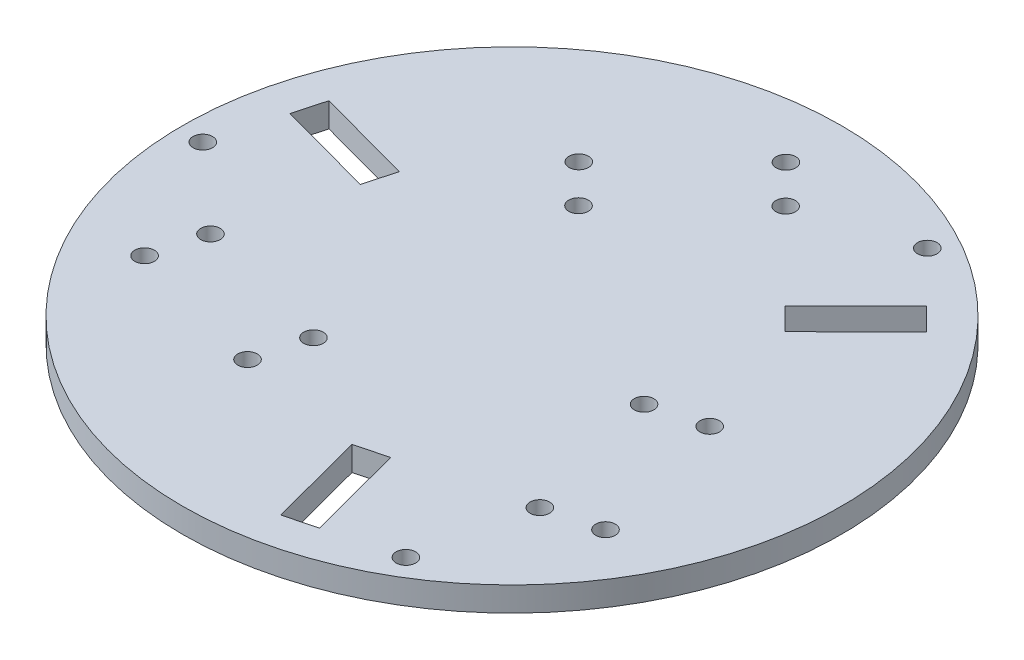
SolidWorks part; units mm, degrees
ref_plane "Front" through (0, 0, 0) normal (0, 0, 1) x (1, 0, 0)
ref_plane "Top" through (0, 0, 0) normal (0, 1, 0) x (1, 0, 0)
ref_plane "Right" through (0, 0, 0) normal (1, 0, 0) x (0, 0, -1)
sketch "Sketch1" plane through (0, 0, 0) normal (0, 1, 0) x (1, 0, 0)
  circle A0 centre (0, 0) radius 67.5
  dimension "D1" = 135
extrude "Boss-Extrude1" add sketch "Sketch1" along normal blind 5
sketch "Sketch7" plane through (0, 5, 0) normal (0, 1, 0) x (1, 0, 0)
  line L0 (-20.4871, 34.1663) -> (-12.7361, 26.361) construction
  line L1 (-12.7361, 26.361) -> (8.551, 47.5) construction
  line L2 (8.551, 47.5) -> (0.8, 55.3053) construction
  line L3 (0.8, 55.3053) -> (-20.4871, 34.1663) construction
  line L4 (0, -2.75) -> (0, 2.75) construction
  line L5 (-2.75, 0) -> (2.75, 0) construction
  line L7 (33.4289, 36.9723) -> (38.009, 32.3601) construction
  line L8 (26.1558, 29.7498) -> (40.702, 44.1948)
  line L9 (26.1558, 29.7498) -> (30.7359, 25.1376)
  line L10 (30.7359, 25.1376) -> (45.2821, 39.5826)
  line L11 (40.702, 44.1948) -> (45.2821, 39.5826)
  circle A0 centre (0.8, 55.3053) radius 2
  circle A1 centre (8.551, 47.5) radius 2
  circle A2 centre (-20.4871, 34.1663) radius 2
  circle A3 centre (-12.7361, 26.361) radius 2
  circle A4 centre (30.5233, 54.5397) radius 2
  circle A5 centre (0, 0) radius 67.5 construction
  point P26 (29.3024, 52.3581)
  dimension "D6" = 4
  dimension "D10" = 4
  dimension "D1" = 11
  dimension "D2" = 30
  dimension "D3" = 0.8
  dimension "D4" = 25
  dimension "D5" = 47.5
  dimension "D7" = 6.5
  dimension "D8" = 20.5
  dimension "D9" = 45.2
  dimension "D11" = 62.5
extrude "Cut-Extrude6" cut sketch "Sketch7" against normal up to next
pattern_circular "CirPattern1" count 3 over 360 about axis through (0, 0, 0) along (0, 1, 0) of "Cut-Extrude6"
